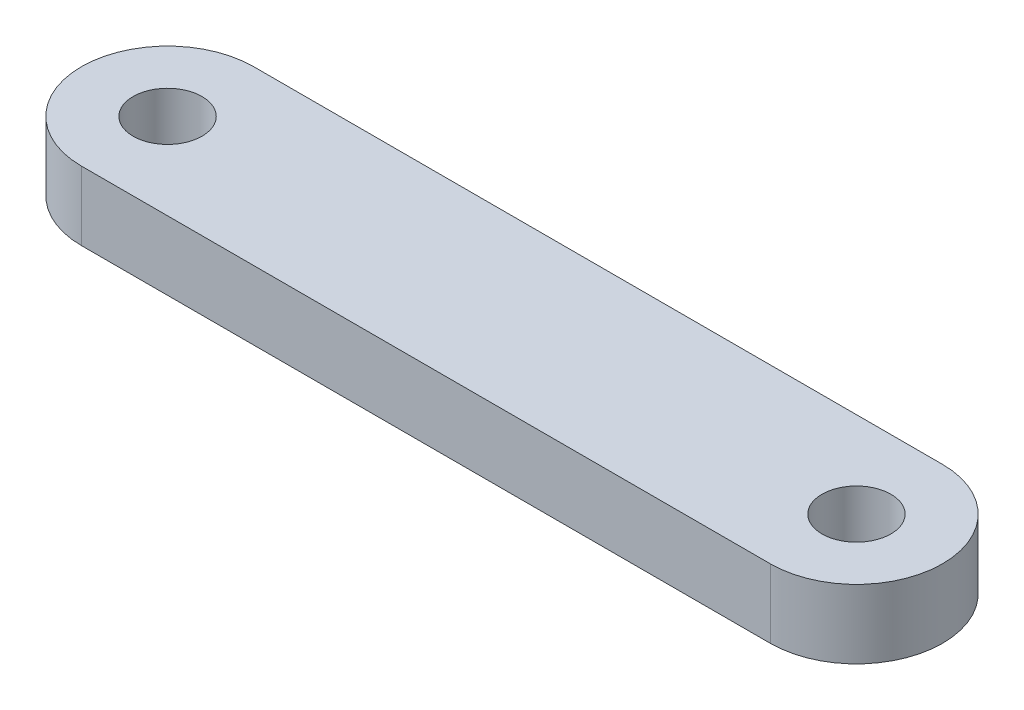
SolidWorks part; units mm, degrees
ref_plane "Front Plane" through (0, 0, 0) normal (0, 0, 1) x (1, 0, 0)
ref_plane "Top Plane" through (0, 0, 0) normal (0, 1, 0) x (1, 0, 0)
ref_plane "Right Plane" through (0, 0, 0) normal (1, 0, 0) x (0, 0, -1)
sketch "Sketch1" plane through (0, 0, 0) normal (0, 1, 0) x (1, 0, 0)
  line L0 (-10, 0) -> (10, 0) construction
  line L1 (-10, 2.5) -> (10, 2.5)
  line L2 (-10, -2.5) -> (10, -2.5)
  arc A0 (-10, 2.5) -> (-10, -2.5) centre (-10, 0) ccw
  arc A1 (10, -2.5) -> (10, 2.5) centre (10, 0) ccw
  circle A2 centre (10, 0) radius 1
  circle A3 centre (-10, 0) radius 1
  point P3 (0, 0)
  dimension "D3" = 2
  dimension "D4" = 2.5
  dimension "D5" = 2
  dimension "D1" = 20
  dimension "D12" = 10
extrude "Boss-Extrude1" add sketch "Sketch1" along normal blind 2
